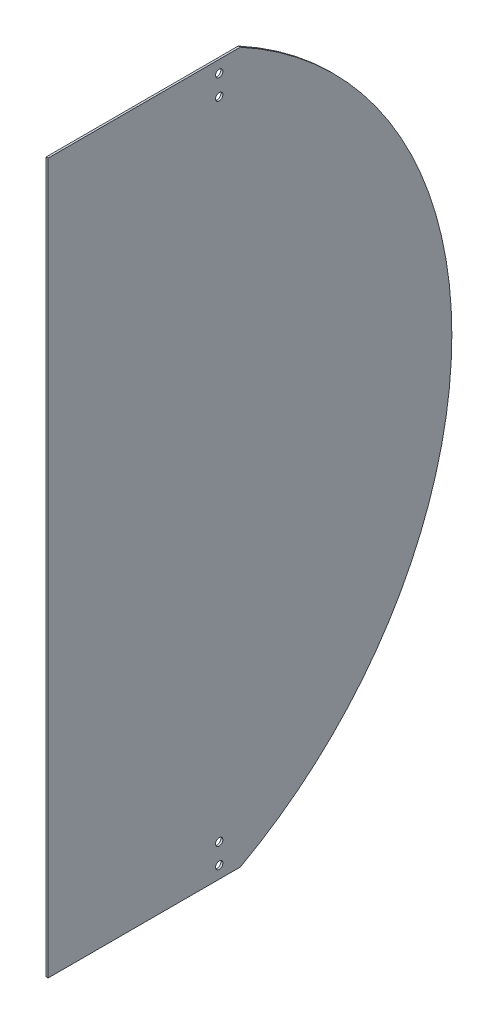
SolidWorks part; units mm, degrees
material "ASTM A36 Steel"
ref_plane "Front Plane" through (0, 0, 0) normal (0, 0, 1) x (1, 0, 0)
ref_plane "Top Plane" through (0, 0, 0) normal (0, 1, 0) x (1, 0, 0)
ref_plane "Right Plane" through (0, 0, 0) normal (1, 0, 0) x (0, 0, -1)
sketch "Sketch1" plane through (0, 0, 0) normal (1, 0, 0) x (0, 0, -1)
  line L1 (0, 438) -> (236.981, 438)
  line L3 (0, -438) -> (236.981, -438)
  line L5 (0, -438) -> (0, 438)
  arc A0 (236.981, -438) -> (236.981, 438) centre (0, 0) ccw
  dimension "D1" = 996
extrude "Boss-Extrude1" add sketch "Sketch1" along normal blind 2.5
sketch "Sketch2" plane through (2.5, 0, 0) normal (1, 0, 0) x (0, 0, -1)
  line L0 (0, 438) -> (0, -438) construction
  line L1 (236.981, 438) -> (0, 438) construction
  circle A0 centre (211, 423) radius 4.5
  dimension "D1" = 9
  dimension "D2" = 211
  dimension "D3" = 15
extrude "Cut-Extrude1" cut sketch "Sketch2" against normal blind 10
pattern_linear "LPattern1" count 2 spacing 25 along (0, -1, 0) of "Cut-Extrude1"
ref_plane "Plane1" through (0, 0, 0) normal (0, 1, 0) x (1, 0, 0)
mirror "Mirror1" about plane through (0, 0, 0) normal (0, 1, 0) of "Cut-Extrude1", "LPattern1"
